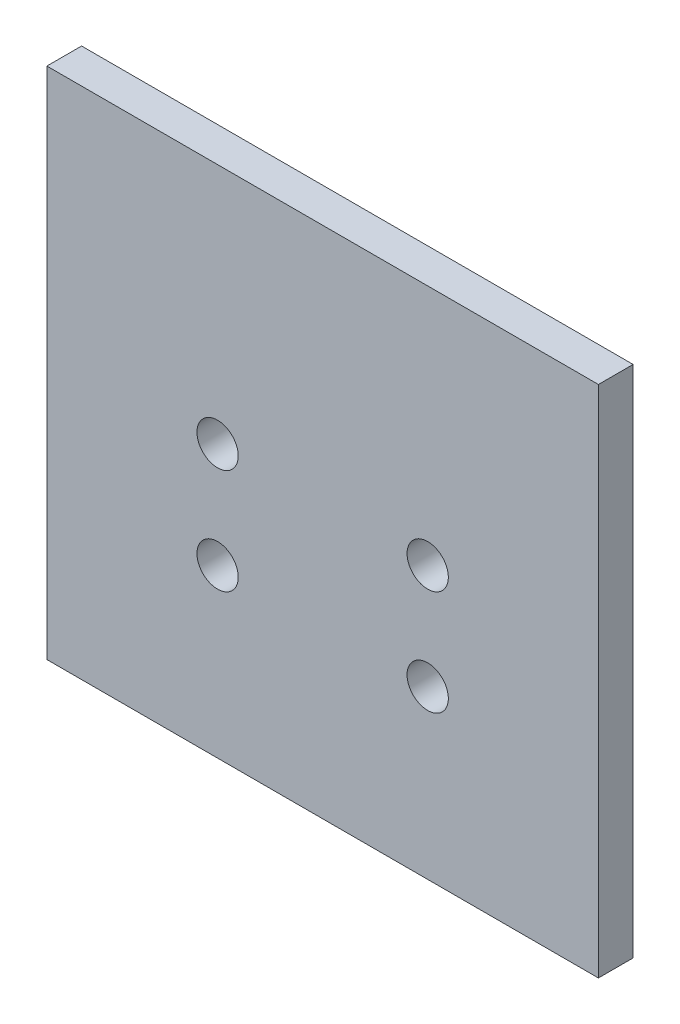
SolidWorks part; units mm, degrees
ref_plane "Front Plane" through (0, 0, 0) normal (0, 0, 1) x (1, 0, 0)
ref_plane "Top Plane" through (0, 0, 0) normal (0, 1, 0) x (1, 0, 0)
ref_plane "Right Plane" through (0, 0, 0) normal (1, 0, 0) x (0, 0, -1)
ref_plane "Plane4" through (0, 0, 9.25) normal (0, 0, 1) x (1, 0, 0)
sketch "Sketch1" plane through (0, 0, 9.25) normal (0, 0, 1) x (1, 0, 0)
  line L0 (-73.5, 68.5) -> (-73.5, -68.5)
  line L1 (-73.5, -68.5) -> (73.5, -68.5)
  line L2 (73.5, -68.5) -> (73.5, 68.5)
  line L3 (73.5, 68.5) -> (-73.5, 68.5)
  circle A0 centre (-28, -24) radius 5.5
  circle A1 centre (28, -24) radius 5.5
  circle A2 centre (28, 4) radius 5.5
  circle A3 centre (-28, 4) radius 5.5
  dimension "D1" = 11
  dimension "D2" = 28
  dimension "D3" = 73.5
  dimension "D4" = 28
  dimension "D5" = 73.5
  dimension "D6" = 4
  dimension "D7" = 68.5
  dimension "D8" = 24
  dimension "D9" = 68.5
extrude "Boss-Extrude1" add sketch "Sketch1" against normal blind 9.25
